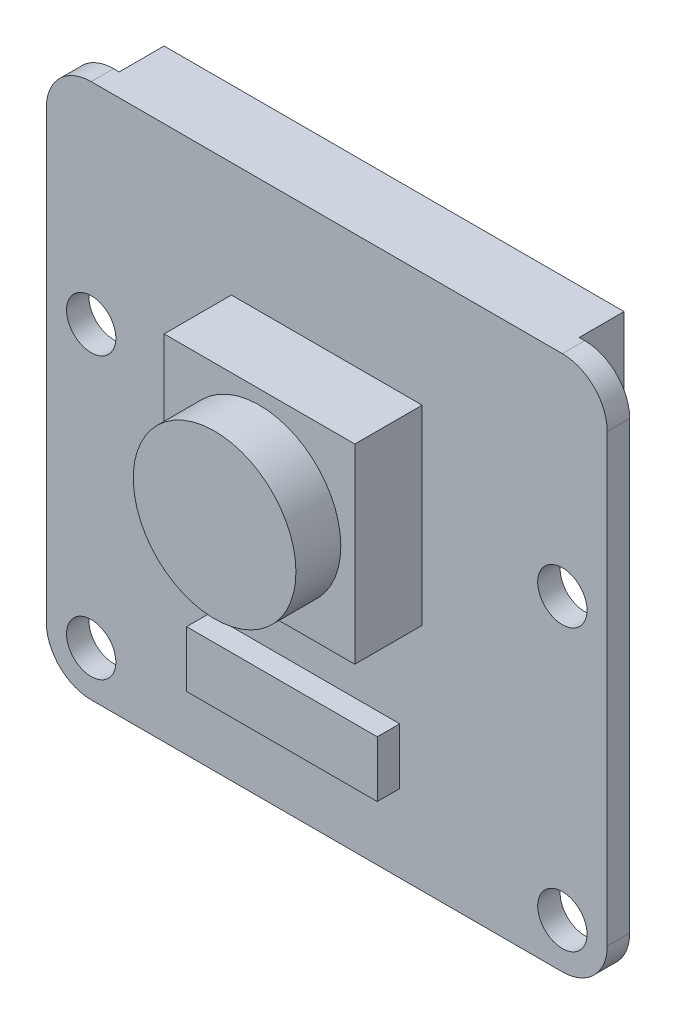
SolidWorks part; units mm, degrees
ref_plane "Front Plane" through (0, 0, 0) normal (0, 0, 1) x (1, 0, 0)
ref_plane "Top Plane" through (0, 0, 0) normal (0, 1, 0) x (1, 0, 0)
ref_plane "Right Plane" through (0, 0, 0) normal (1, 0, 0) x (0, 0, -1)
sketch "Sketch1" plane through (0, 0, 0) normal (0, 0, 1) x (1, 0, 0)
  line L1 (-12.5, 11.931) -> (12.5, 11.931)
  line L2 (-12.5, 11.931) -> (-12.5, -11.931)
  line L3 (-12.5, -11.931) -> (12.5, -11.931)
  line L4 (12.5, 11.931) -> (12.5, -11.931)
  line L5 (-12.5, 11.931) -> (12.5, -11.931) construction
  line L6 (-12.5, -11.931) -> (12.5, 11.931) construction
  point P0 (0, 0)
  dimension "D1" = 23.862
  dimension "D2" = 25
extrude "Boss-Extrude1" add sketch "Sketch1" along normal blind 1
fillet "Fillet1" radius 2 4 edges at (12.5, 11.931, 0.5) (12.5, -11.931, 0.5) (-12.5, -11.931, 0.5) (-12.5, 11.931, 0.5)
sketch "Sketch2" plane through (0, 0, 1) normal (0, 0, 1) x (1, 0, 0)
  line L0 (12.5, -9.931) -> (12.5, 9.931) construction
  line L1 (-10.5, -11.931) -> (10.5, -11.931) construction
  circle A0 centre (-10.5, -9.931) radius 1.1
  circle A1 centre (10.5, -9.931) radius 1.1
  circle A2 centre (10.5, 2.569) radius 1.1
  circle A3 centre (-10.5, 2.569) radius 1.1
  dimension "D7" = 2.2
  dimension "D8" = 2.2
  dimension "D9" = 2.2
  dimension "D10" = 2.2
  dimension "D1" = 2
  dimension "D2" = 2
  dimension "D3" = 21
  dimension "D4" = 21
  dimension "D5" = 2
  dimension "D6" = 12.5
extrude "Cut-Extrude1" cut sketch "Sketch2" against normal blind 1
sketch "Sketch3" plane through (0, 0, 1) normal (0, 0, 1) x (1, 0, 0)
  line L0 (12.5, -9.931) -> (12.5, 9.931) construction
  line L1 (-5.25, -5.981) -> (3.25, -5.981)
  line L2 (-5.25, -5.981) -> (-5.25, -8.481)
  line L3 (-5.25, -8.481) -> (3.25, -8.481)
  line L4 (3.25, -5.981) -> (3.25, -8.481)
  line L5 (-5.25, -5.981) -> (3.25, -8.481) construction
  line L6 (-5.25, -8.481) -> (3.25, -5.981) construction
  line L7 (-10.5, -11.931) -> (10.5, -11.931) construction
  line L9 (-4.25, 6.819) -> (4.25, 6.819)
  line L10 (-4.25, 6.819) -> (-4.25, -1.681)
  line L11 (-4.25, -1.681) -> (4.25, -1.681)
  line L12 (4.25, 6.819) -> (4.25, -1.681)
  line L13 (-4.25, 6.819) -> (4.25, -1.681) construction
  line L14 (-4.25, -1.681) -> (4.25, 6.819) construction
  point P0 (-1, -7.231)
  point P10 (0, 2.569)
  dimension "D1" = 2.5
  dimension "D2" = 8.5
  dimension "D3" = 13.5
  dimension "D4" = 4.7
  dimension "D5" = 8.5
  dimension "D6" = 8.5
  dimension "D7" = 14.5
  dimension "D8" = 12.5
extrude "Boss-Extrude2" add sketch "Sketch3" along normal blind 1
sketch "Sketch4" plane through (0, 0, 2) normal (0, 0, 1) x (1, 0, 0)
  line L1 (-4.25, 6.819) -> (4.25, 6.819)
  line L2 (-4.25, 6.819) -> (-4.25, -1.681)
  line L3 (-4.25, -1.681) -> (4.25, -1.681)
  line L4 (4.25, 6.819) -> (4.25, -1.681)
extrude "Boss-Extrude3" add sketch "Sketch4" along normal blind 2
sketch "Sketch5" plane through (0, 0, 4) normal (0, 0, 1) x (1, 0, 0)
  line L0 (4.25, -1.681) -> (4.25, 6.819) construction
  line L2 (-4.25, -1.681) -> (4.25, -1.681) construction
  circle A0 centre (0, 2.569) radius 3.625
  dimension "D3" = 7.25
  dimension "D1" = 4.25
  dimension "D2" = 4.25
extrude "Boss-Extrude4" add sketch "Sketch5" along normal blind 2
sketch "Sketch6" plane through (0, 0, 0) normal (0, 0, -1) x (-1, 0, 0)
  line L0 (-10.5, 11.931) -> (10.5, 11.931) construction
  line L1 (-12.5, -9.931) -> (-12.5, 9.931) construction
  line L2 (-10.25, 11.931) -> (10.25, 11.931)
  line L3 (-10.25, 11.931) -> (-10.25, 6.431)
  line L4 (-10.25, 6.431) -> (10.25, 6.431)
  line L5 (10.25, 11.931) -> (10.25, 6.431)
  dimension "D1" = 20.5
  dimension "D2" = 2.25
  dimension "D3" = 5.5
extrude "Boss-Extrude5" add sketch "Sketch6" along normal blind 2
